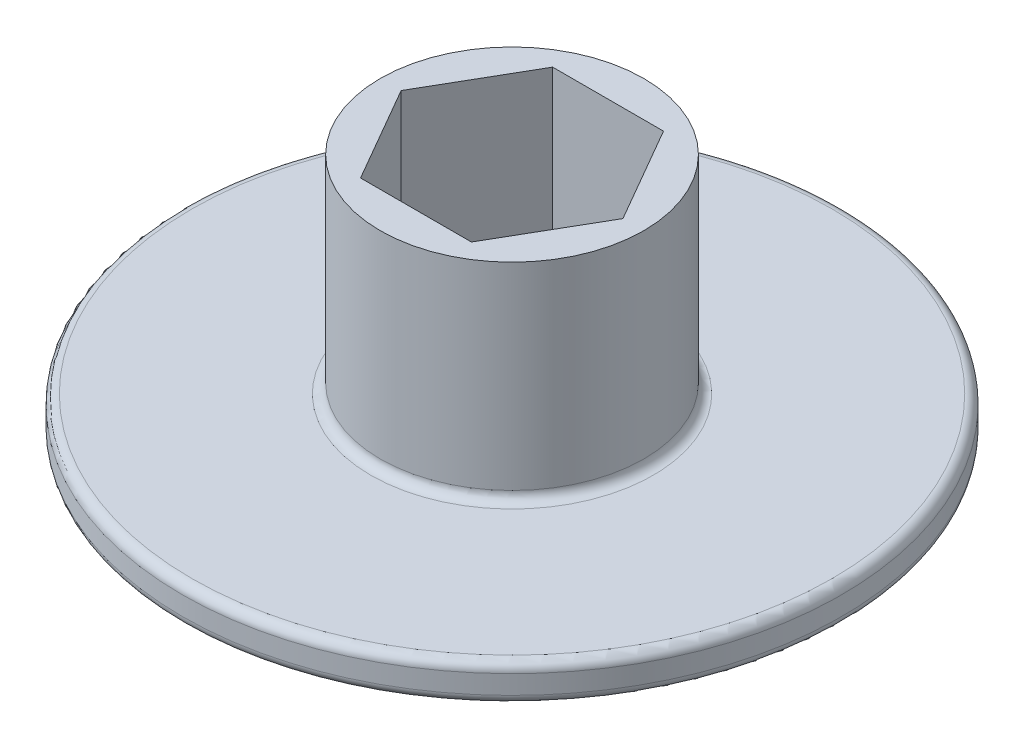
SolidWorks part; units mm, degrees
ref_plane "Front Plane" through (0, 0, 0) normal (0, 0, 1) x (1, 0, 0)
ref_plane "Top Plane" through (0, 0, 0) normal (0, 1, 0) x (1, 0, 0)
ref_plane "Right Plane" through (0, 0, 0) normal (1, 0, 0) x (0, 0, -1)
sketch "Sketch1" plane through (0, 0, 0) normal (0, 1, 0) x (1, 0, 0)
  line L1 (7.479, 0) -> (3.7395, 6.477)
  line L2 (3.7395, 6.477) -> (-3.7395, 6.477)
  line L3 (-3.7395, 6.477) -> (-7.479, 0)
  line L4 (-7.479, 0) -> (-3.7395, -6.477)
  line L5 (-3.7395, -6.477) -> (3.7395, -6.477)
  line L6 (3.7395, -6.477) -> (7.479, 0)
  circle A0 centre (0, 0) radius 6.477 construction
  circle A1 centre (0, 0) radius 22.225
  dimension "D2" = 44.45
  dimension "D1" = 12.954
extrude "Boss-Extrude1" add sketch "Sketch1" along normal blind 2.54
sketch "Sketch2" plane through (0, 2.54, 0) normal (0, 1, 0) x (1, 0, 0)
  line L1 (3.7395, 6.477) -> (-3.7395, 6.477)
  line L2 (-3.7395, 6.477) -> (-7.479, 0)
  line L3 (-7.479, 0) -> (-3.7395, -6.477)
  line L4 (-3.7395, -6.477) -> (3.7395, -6.477)
  line L5 (3.7395, -6.477) -> (7.479, 0)
  line L6 (7.479, 0) -> (3.7395, 6.477)
  circle A1 centre (0, 0) radius 6.477 construction
  circle A2 centre (0, 0) radius 8.89
  dimension "D1" = 17.78
extrude "Boss-Extrude2" add sketch "Sketch2" along normal blind 13.97
fillet "Fillet1" radius 0.635 9 edges at (0, 2.54, 8.89) (0, 2.54, 22.225) (0, 0, 6.477) (-5.6092, 0, 3.2385) (-5.6092, 0, -3.2385) (0, 0, -6.477) (5.6092, 0, -3.2385) (5.6092, 0, 3.2385) (0, 0, 22.225)
